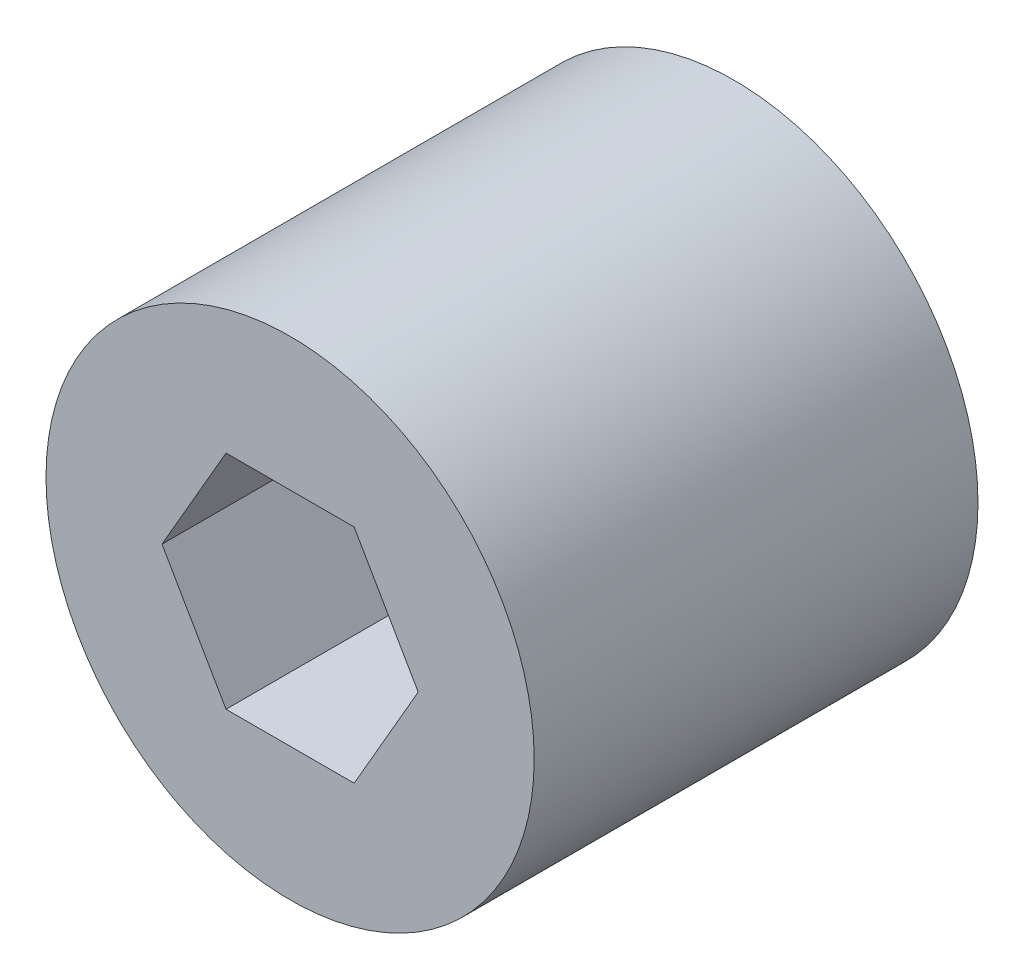
SolidWorks part; units mm, degrees
ref_plane "Front Plane" through (0, 0, 0) normal (0, 0, 1) x (1, 0, 0)
ref_plane "Top Plane" through (0, 0, 0) normal (0, 1, 0) x (1, 0, 0)
ref_plane "Right Plane" through (0, 0, 0) normal (1, 0, 0) x (0, 0, -1)
sketch "Sketch2" plane through (0, 0, 0) normal (0, 0, 1) x (1, 0, 0)
  line L0 (0, 0) -> (16.4829, 0) construction
  line L1 (-3.6662, 6.35) -> (-7.3323, 0)
  line L2 (-7.3323, 0) -> (-3.6662, -6.35)
  line L3 (-3.6662, -6.35) -> (3.6662, -6.35)
  line L4 (3.6662, -6.35) -> (7.3323, 0)
  line L5 (7.3323, 0) -> (3.6662, 6.35)
  line L6 (3.6662, 6.35) -> (-3.6662, 6.35)
  circle A0 centre (0, 0) radius 13.97
  circle A1 centre (0, 0) radius 6.35 construction
  dimension "D1" = 27.94
  dimension "D2" = 12.7
extrude "Boss-Extrude1" add sketch "Sketch2" against normal blind 25.4
